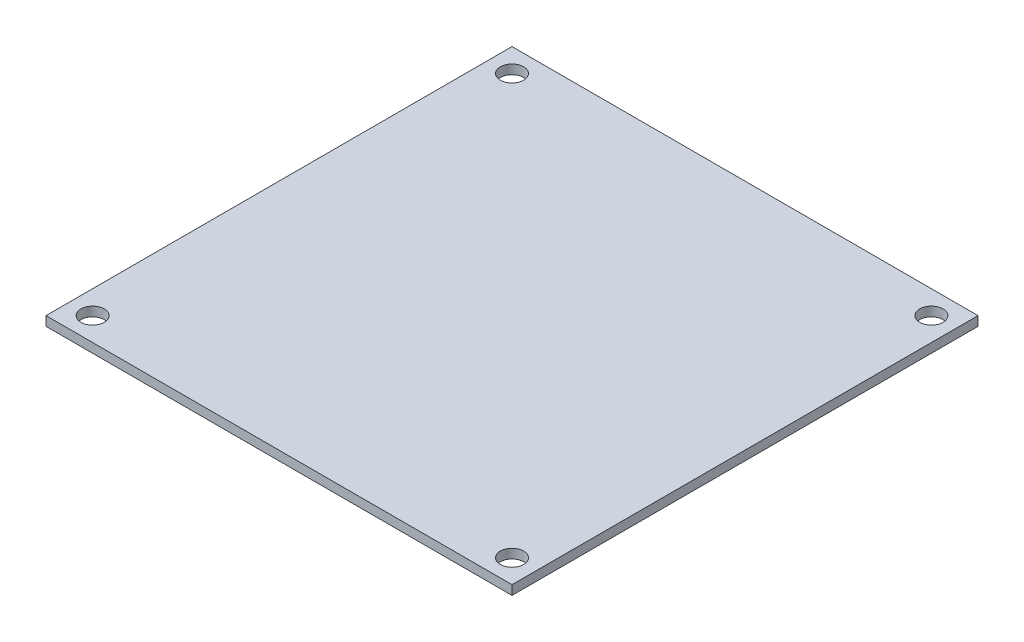
SolidWorks part; units mm, degrees
ref_plane "Plan de face" through (0, 0, 0) normal (0, 0, 1) x (1, 0, 0)
ref_plane "Plan de dessus" through (0, 0, 0) normal (0, 1, 0) x (1, 0, 0)
ref_plane "Plan de droite" through (0, 0, 0) normal (1, 0, 0) x (0, 0, -1)
sketch "Esquisse1" plane through (0, 0, 0) normal (0, 1, 0) x (1, 0, 0)
  line L0 (0, 40) -> (0, 0) construction
  line L1 (-40, 40) -> (40, 40)
  line L2 (-40, 40) -> (-40, -40)
  line L3 (-40, -40) -> (40, -40)
  line L4 (40, 40) -> (40, -40)
  line L5 (0, 0) -> (40, 0) construction
  circle A0 centre (-36, 36) radius 2
  circle A1 centre (36, 36) radius 2
  circle A2 centre (36, -36) radius 2
  circle A3 centre (-36, -36) radius 2
  dimension "D2" = 4
  dimension "D1" = 80
  dimension "D3" = 4
  dimension "D4" = 4
extrude "Extrusion1" add sketch "Esquisse1" along normal blind 1.6
